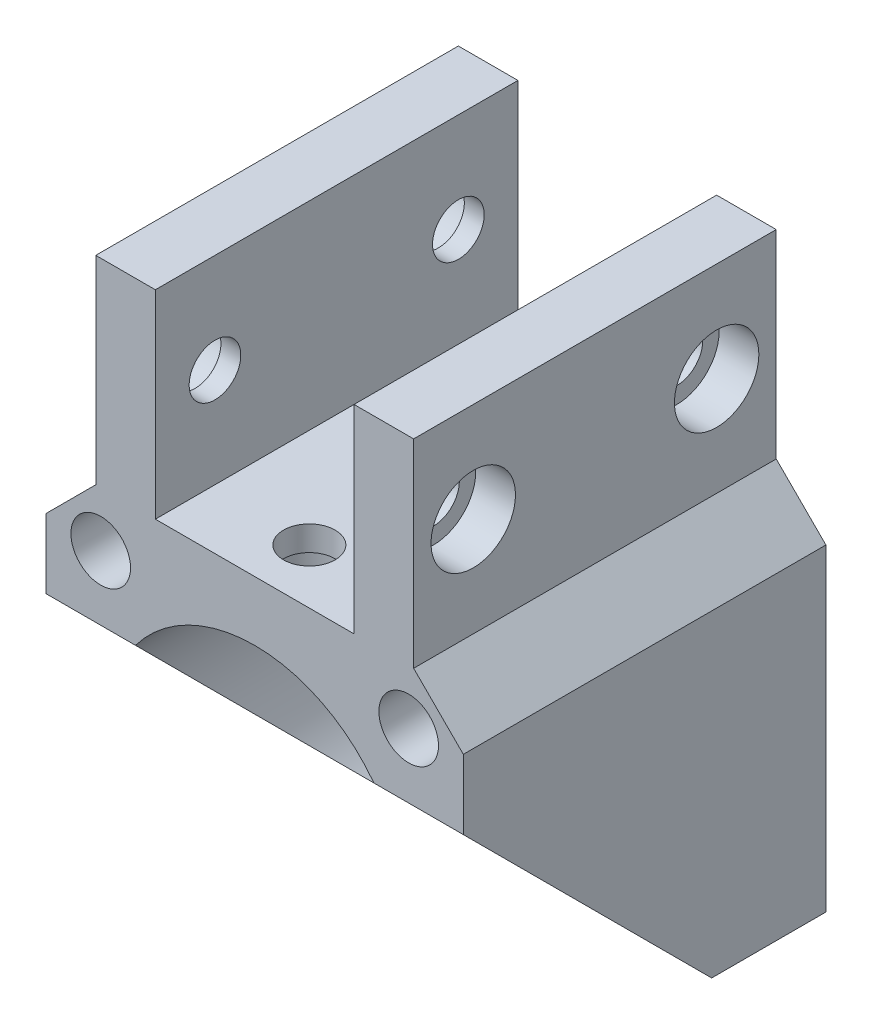
SolidWorks part; units mm, degrees
ref_plane "前基準面" through (0, 0, 0) normal (0, 0, 1) x (1, 0, 0)
ref_plane "上基準面" through (0, 0, 0) normal (0, 1, 0) x (1, 0, 0)
ref_plane "右基準面" through (0, 0, 0) normal (1, 0, 0) x (0, 0, -1)
sketch "草圖1" plane through (0, 0, 0) normal (0, 0, 1) x (1, 0, 0)
  line L1 (-21, 21) -> (21, 21)
  line L2 (-21, 21) -> (-21, -21)
  line L3 (-21, -21) -> (21, -21)
  line L4 (21, 21) -> (21, -21)
  point P4 (0, 21)
  point P6 (-21, 0)
  dimension "D1" = 42
  dimension "D2" = 42
extrude "填料-伸長1" add sketch "草圖1" along normal blind 6.5
sketch "草圖5" plane through (21, 0, 0) normal (1, 0, 0) x (0, 0, -1)
  line L0 (-6.5, -21) -> (-48.5, 21)
  line L1 (-48.5, 21) -> (-6.5, 21)
  line L2 (-6.5, 21) -> (-6.5, -21)
  dimension "D1" = 42
  dimension "D2" = 42
extrude "填料-伸長2" add sketch "草圖5" against normal up to surface (42 mm away) up to face at (-21, 0, 3.25)
sketch "草圖2" plane through (0, 0, 0) normal (0, 0, 1) x (1, 0, 0)
  circle A0 centre (0, 0) radius 15
  dimension "D1" = 30
extrude "除料-伸長2" cut sketch "草圖2" along normal through all
sketch "草圖4" plane through (0, 0, 0) normal (0, 0, 1) x (1, 0, 0)
  line L2 (0, 21) -> (0, -21) construction
  line L4 (0, -21) -> (21, 0) construction
  line L6 (21, 0) -> (-21, 0) construction
  circle A0 centre (-15.5, 15.5) radius 1.75
  circle A1 centre (-15.5, -15.5) radius 1.75
  circle A2 centre (15.5, -15.5) radius 1.75
  circle A3 centre (15.5, 15.5) radius 1.75
  dimension "D1" = 3.5
  dimension "D4" = 31
extrude "除料-伸長1" cut sketch "草圖4" along normal through all
chamfer "導角1" distance 5 angle 45 4 edges at (21, -21, 3.25) (-21, -21, 3.25) (-21, 21, 24.25) (21, 21, 24.25)
sketch "草圖6" plane through (-21, 0, 0) normal (-1, 0, 0) x (0, 0, 1)
  line L0 (48.5, 21) -> (36.5, 21)
  line L2 (0, 21) -> (48.5, 21) construction
  line L3 (36.5, 21) -> (36.5, 9)
  line L4 (11.5, -16) -> (43.5, 16) construction
  line L5 (36.5, 9) -> (48.5, 21)
  dimension "D1" = 12
extrude "除料-伸長3" cut sketch "草圖6" against normal through all
sketch "草圖7" plane through (0, 0, 36.5) normal (0, 0, 1) x (1, 0, 0)
  circle A0 centre (-15.5, 15.5) radius 3
  circle A1 centre (15.5, 15.5) radius 3
  circle A2 centre (15.5, -15.5) radius 3
  circle A3 centre (-15.5, -15.5) radius 3
  point P12 (0, 0)
  dimension "D1" = 6
  dimension "D2" = 4
extrude "除料-伸長4" cut sketch "草圖7" against normal blind 31.5
sketch "草圖8" plane through (0, 0, 0) normal (0, 1, 0) x (1, 0, 0)
  line L0 (0, 0) -> (0, -36.5) construction
  line L1 (-16, 0) -> (16, 0) construction
  line L3 (-12, -36.5) -> (12, -36.5) construction
  circle A0 centre (0, -15) radius 2.6
  circle A1 centre (0, -31) radius 2.6
  point P4 (0, -36.5)
  point P8 (0, -43.5)
  dimension "D1" = 5.2
  dimension "D2" = 5.2
  dimension "D3" = 15
  dimension "D4" = 16
extrude "除料-伸長5" cut sketch "草圖8" against normal blind 5 and the other way through all
sketch "草圖9" plane through (0, 0, 0) normal (0, 1, 0) x (1, 0, 0)
  circle A0 centre (0, -31) radius 4.25
  circle A1 centre (0, -15) radius 4.25
  dimension "D1" = 8.5
  dimension "D2" = 8.5
extrude "除料-伸長6" cut sketch "草圖9" along normal blind 18.5
sketch "草圖10" plane through (0, 0, 0) normal (0, 0, -1) x (-1, 0, 0)
  circle A0 centre (0, 0) radius 15
  circle A1 centre (0, 0) radius 11.5
  dimension "D1" = 23
extrude "填料-伸長3" add sketch "草圖10" against normal blind 3
sketch "草圖11" plane through (0, 21, 0) normal (0, 1, 0) x (1, 0, 0)
  line L0 (16, 0) -> (-16, 0) construction
  line L1 (16, -36.5) -> (10, -36.5)
  line L2 (16, -36.5) -> (16, 0)
  line L3 (16, 0) -> (10, 0)
  line L4 (10, -36.5) -> (10, 0)
  line L6 (-16, -36.5) -> (-10, -36.5)
  line L7 (-16, -36.5) -> (-16, 0)
  line L8 (-16, 0) -> (-10, 0)
  line L9 (-10, -36.5) -> (-10, 0)
  dimension "D1" = 20
  dimension "D2" = 6
  dimension "D3" = 6
extrude "填料-伸長4" add sketch "草圖11" along normal blind 20
sketch "草圖12" plane through (16, 0, 0) normal (1, 0, 0) x (0, 0, -1)
  line L0 (-36.5, 41) -> (-36.5, 21) construction
  line L1 (0, 41) -> (0, 21) construction
  circle A0 centre (-30.5, 31) radius 2.6
  circle A1 centre (-6, 31) radius 2.6
  dimension "D1" = 5.2
  dimension "D2" = 5.2
  dimension "D3" = 6
  dimension "D4" = 6
extrude "除料-伸長7" cut sketch "草圖12" against normal through all both and the other way through all
sketch "草圖13" plane through (16, 0, 0) normal (1, 0, 0) x (0, 0, -1)
  circle A0 centre (-30.5, 31) radius 4.25
  circle A1 centre (-6, 31) radius 4.25
  dimension "D1" = 8.5
  dimension "D2" = 8.5
extrude "除料-伸長8" cut sketch "草圖13" against normal blind 4
sketch "草圖14" plane through (-16, 0, 0) normal (-1, 0, 0) x (0, 0, 1)
  circle A0 centre (30.5, 31) radius 4.25
  circle A1 centre (6, 31) radius 4.25
  dimension "D1" = 8.5
  dimension "D2" = 8.5
extrude "除料-伸長9" cut sketch "草圖14" against normal blind 4
